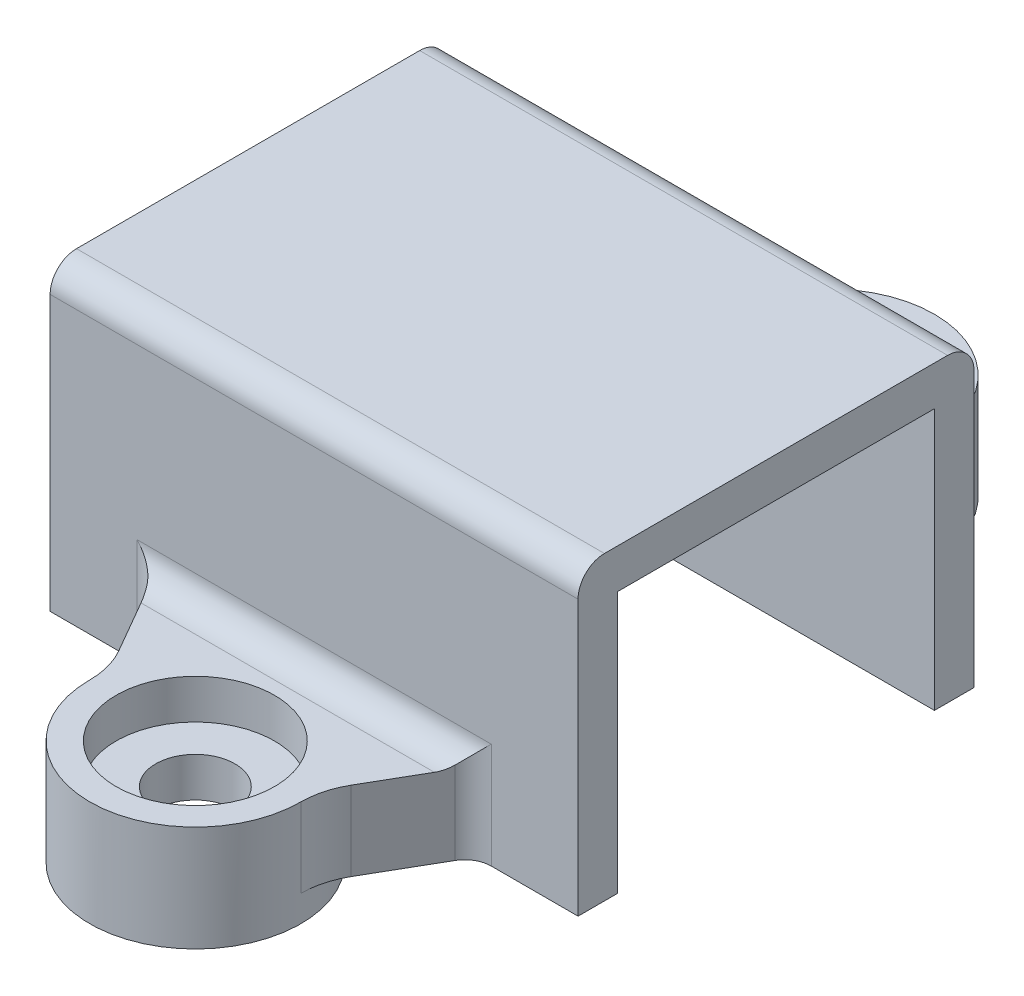
SolidWorks part; units mm, degrees
ref_plane "Front Plane" through (0, 0, 0) normal (0, 0, 1) x (1, 0, 0)
ref_plane "Top Plane" through (0, 0, 0) normal (0, 1, 0) x (1, 0, 0)
ref_plane "Right Plane" through (0, 0, 0) normal (1, 0, 0) x (0, 0, -1)
sketch "Sketch1" plane through (0, 0, 0) normal (1, 0, 0) x (0, 0, -1)
  line L0 (-6, 0) -> (-7.5, 0)
  line L1 (-4, 9.9) -> (4, 9.9)
  line L2 (-6, 7.9) -> (-6, 0)
  line L3 (-6, 0) -> (6, 0) construction
  line L4 (6, 7.9) -> (6, 0)
  line L5 (-7.5, 0) -> (-7.5, 10.4)
  line L6 (-6.5, 11.4) -> (6.5, 11.4)
  line L7 (7.5, 10.4) -> (7.5, 0)
  line L8 (7.5, 0) -> (6, 0)
  arc A0 (4, 9.9) -> (6, 7.9) centre (4, 7.9) cw
  arc A1 (-4, 9.9) -> (-6, 7.9) centre (-4, 7.9) ccw
  arc A2 (6.5, 11.4) -> (7.5, 10.4) centre (6.5, 10.4) cw
  arc A3 (-7.5, 10.4) -> (-6.5, 11.4) centre (-6.5, 10.4) cw
  point P7 (6, 9.9)
  dimension "D3" = 2
  dimension "D7" = 1
  dimension "D1" = 9.9
  dimension "D2" = 12
  dimension "D4" = 1.5
  dimension "D5" = 1.5
  dimension "D6" = 1.5
extrude "Boss-Extrude1" add sketch "Sketch1" along normal mid plane 20
sketch "Sketch2" plane through (0, 9.9, 0) normal (0, -1, 0) x (1, 0, 0)
  line L0 (0, 0) -> (4.5, 0) construction
  line L1 (4.9, -6) -> (4.1, -6)
  line L2 (4.9, -6) -> (4.9, 6) construction
  line L3 (4.9, 6) -> (4.1, 6)
  line L4 (4.1, -6) -> (4.1, 6)
  line L5 (4.9, -6) -> (4.1, 6) construction
  line L6 (4.9, 6) -> (4.1, -6) construction
  line L7 (10, 4) -> (10, -4) construction
  line L8 (1.9, -6) -> (1.1, -6)
  line L9 (1.9, -6) -> (1.9, 6)
  line L10 (1.9, 6) -> (1.1, 6)
  line L11 (1.1, -6) -> (1.1, 6)
  line L12 (1.9, -6) -> (1.1, 6) construction
  line L13 (1.9, 6) -> (1.1, -6) construction
  line L14 (4.9, -6) -> (11.8688, -6)
  line L15 (11.8688, -6) -> (11.8688, 6)
  line L16 (11.8688, 6) -> (4.9, 6)
  point P0 (4.5, 0)
  point P7 (1.5, 0)
  dimension "D1" = 12
  dimension "D2" = 0.8
  dimension "D3" = 5.1
  dimension "D4" = 2.2
extrude "Cut-Extrude1" cut sketch "Sketch2" along normal blind 10
sketch "Sketch3" plane through (0, 0, 0) normal (0, 1, 0) x (1, 0, 0)
  line L0 (0, -12) -> (0, 12) construction
  line L1 (-6.134, 7.5) -> (-4.4019, 10.5)
  line L2 (10, 7.5) -> (-10, 7.5) construction
  line L3 (6.134, 7.5) -> (4.4019, 10.5)
  line L4 (0, 0) -> (-5.914, 0) construction
  line L5 (6.134, -7.5) -> (4.4019, -10.5)
  line L6 (-6.134, -7.5) -> (-4.4019, -10.5)
  line L7 (-6.134, -7.5) -> (6.134, -7.5)
  line L8 (-6.134, 7.5) -> (6.134, 7.5)
  circle A0 centre (0, 12) radius 1.5
  circle A1 centre (0, -12) radius 1.5
  arc A2 (4, 12) -> (-4, 12) centre (0, 12) ccw
  arc A3 (-4, 12) -> (-4.4019, 10.5) centre (-7, 12) cw
  arc A4 (4, -12) -> (4.4019, -10.5) centre (7, -12) cw
  arc A5 (4, 12) -> (4.4019, 10.5) centre (7, 12) ccw
  arc A6 (4, -12) -> (-4, -12) centre (0, -12) cw
  arc A7 (-4, -12) -> (-4.4019, -10.5) centre (-7, -12) ccw
  point P4 (0, 0)
  dimension "D1" = 3
  dimension "D3" = 8
  dimension "D4" = 3
  dimension "D2" = 24
  dimension "D5" = 30
extrude "Boss-Extrude2" add sketch "Sketch3" along normal blind 3
fillet "Fillet1" radius 1 6 edges at (6.134, 1.5, -7.5) (-6.134, 1.5, -7.5) (-6.134, 1.5, 7.5) (6.134, 1.5, 7.5) (0, 3, 7.5) (0, 3, -7.5)
sketch "Sketch4" plane through (0, 3, 0) normal (0, 1, 0) x (1, 0, 0)
  circle A0 centre (0, -12) radius 3
  circle A1 centre (0, 12) radius 3
  dimension "D1" = 6
  dimension "D2" = 6
extrude "Cut-Extrude2" cut sketch "Sketch4" against normal blind 1.5
sketch "Sketch6" plane through (0, 0, 0) normal (0, -1, 0) x (1, 0, 0)
  circle A0 centre (0, 12) radius 4
  circle A1 centre (0, 12) radius 3.05
  circle A2 centre (0, -12) radius 4
  circle A3 centre (0, -12) radius 3.05
  dimension "D1" = 8
  dimension "D2" = 6.1
extrude "Boss-Extrude3" add sketch "Sketch6" along normal blind 1
